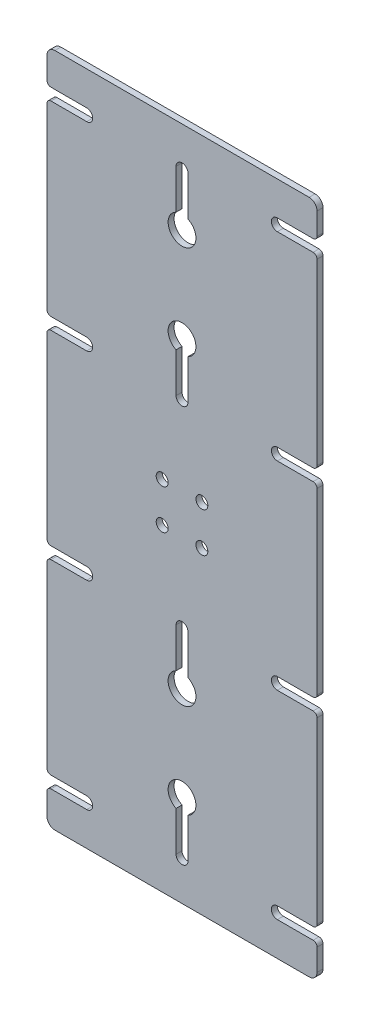
SolidWorks part; units mm, degrees
ref_plane "前视基准面" through (0, 0, 0) normal (0, 0, 1) x (1, 0, 0)
ref_plane "上视基准面" through (0, 0, 0) normal (0, 1, 0) x (1, 0, 0)
ref_plane "右视基准面" through (0, 0, 0) normal (1, 0, 0) x (0, 0, -1)
sketch "草图1" plane through (0, 0, 0) normal (0, 0, 1) x (1, 0, 0)
  line L0 (80, 90) -> (100, 90)
  line L1 (0, 0) -> (80, 0)
  line L2 (0, 0) -> (0, 70)
  line L3 (0, 160) -> (80, 160)
  line L4 (80, 0) -> (80, 70)
  line L5 (100, 90) -> (100, 70)
  line L6 (100, 70) -> (80, 70)
  line L7 (0, 70) -> (-20, 70)
  line L8 (-20, 70) -> (-20, 90)
  line L9 (-20, 90) -> (0, 90)
  line L10 (0, 90) -> (0, 160)
  line L11 (80, 90) -> (80, 160)
  dimension "D1" = 160
  dimension "D2" = 80
  dimension "D3" = 20
  dimension "D4" = 20
  dimension "D5" = 20
  dimension "D6" = 20
  dimension "D7" = 70
extrude "凸台-拉伸1" add sketch "草图1" along normal blind 1.5
sketch "草图2" plane through (0, 0, 1.5) normal (0, 0, 1) x (1, 0, 0)
  line L0 (0, 0) -> (80, 0) construction
  line L1 (0, 70) -> (0, 0) construction
  line L2 (64, 153.5) -> (80, 153.5)
  line L3 (38.5, 5) -> (38.5, 15)
  line L4 (80, 90) -> (80, 160) construction
  line L5 (64, 156.5) -> (80, 156.5)
  line L6 (16, 153.5) -> (0, 153.5)
  line L7 (0, 160) -> (0, 90) construction
  line L8 (16, 156.5) -> (0, 156.5)
  line L9 (64, 103.5) -> (80, 103.5)
  line L10 (64, 106.5) -> (80, 106.5)
  line L11 (16, 106.5) -> (0, 106.5)
  line L12 (16, 103.5) -> (0, 103.5)
  line L13 (16, 56.5) -> (0, 56.5)
  line L14 (16, 53.5) -> (0, 53.5)
  line L15 (64, 53.5) -> (80, 53.5)
  line L16 (80, 0) -> (80, 70) construction
  line L17 (64, 56.5) -> (80, 56.5)
  line L18 (16, 6.5) -> (0, 6.5)
  line L19 (16, 3.5) -> (0, 3.5)
  line L20 (64, 6.5) -> (80, 6.5)
  line L21 (64, 3.5) -> (80, 3.5)
  line L22 (80, 156.5) -> (80, 153.5)
  line L23 (0, 156.5) -> (0, 153.5)
  line L24 (0, 106.5) -> (0, 103.5)
  line L25 (80, 106.5) -> (80, 103.5)
  line L26 (80, 56.5) -> (80, 53.5)
  line L27 (0, 56.5) -> (0, 53.5)
  line L28 (0, 6.5) -> (0, 3.5)
  line L29 (80, 6.5) -> (80, 3.5)
  line L30 (41.5, 5) -> (41.5, 15)
  line L31 (32.0717, 15) -> (48.9361, 15) construction
  line L32 (40, 19.8903) -> (40, 12.1937) construction
  line L33 (6.3154, 80) -> (80, 80) construction
  line L34 (40, 113.7367) -> (40, 124.7584) construction
  line L35 (38.5, 155) -> (38.5, 145)
  line L36 (41.5, 155) -> (41.5, 145)
  line L37 (41.5, 55) -> (41.5, 45)
  line L38 (38.5, 55) -> (38.5, 45)
  line L39 (40, 46.2633) -> (40, 35.2416) construction
  line L40 (38.5, 105) -> (38.5, 115)
  line L41 (41.5, 105) -> (41.5, 115)
  arc A0 (64, 6.5) -> (64, 3.5) centre (64, 5) ccw
  arc A1 (64, 56.5) -> (64, 53.5) centre (64, 55) ccw
  arc A2 (64, 106.5) -> (64, 103.5) centre (64, 105) ccw
  arc A3 (64, 156.5) -> (64, 153.5) centre (64, 155) ccw
  arc A4 (16, 153.5) -> (16, 156.5) centre (16, 155) ccw
  arc A5 (16, 103.5) -> (16, 106.5) centre (16, 105) ccw
  arc A6 (16, 53.5) -> (16, 56.5) centre (16, 55) ccw
  arc A7 (16, 3.5) -> (16, 6.5) centre (16, 5) ccw
  arc A8 (41.5, 155) -> (38.5, 155) centre (40, 155) ccw
  arc A9 (38.5, 105) -> (41.5, 105) centre (40, 105) ccw
  arc A10 (41.5, 55) -> (38.5, 55) centre (40, 55) ccw
  arc A11 (38.5, 5) -> (41.5, 5) centre (40, 5) ccw
  arc A12 (41.5, 15) -> (38.5, 15) centre (40, 18.1623) ccw
  arc A13 (41.5, 145) -> (38.5, 145) centre (40, 141.8377) cw
  arc A14 (38.5, 45) -> (41.5, 45) centre (40, 41.8377) ccw
  arc A15 (38.5, 115) -> (41.5, 115) centre (40, 118.1623) cw
  dimension "D1" = 3
  dimension "D2" = 3
  dimension "D3" = 3
  dimension "D4" = 3
  dimension "D11" = 10
  dimension "D13" = 7
  dimension "D14" = 3
  dimension "D15" = 40
  dimension "D23" = 7
  dimension "D5" = 16
  dimension "D6" = 16
  dimension "D7" = 16
  dimension "D8" = 5
  dimension "D9" = 2
  dimension "D10" = 16
  dimension "D16" = 16
  dimension "D17" = 50
  dimension "D18" = 50
  dimension "D19" = 50
  dimension "D20" = 80
  dimension "D21" = 10
  dimension "D22" = 1.5
extrude "切除-拉伸1" cut sketch "草图2" against normal blind 1.5
sketch "草图3" plane through (0, 0, 1.5) normal (0, 0, 1) x (1, 0, 0)
  line L0 (0, 90) -> (-20, 90) construction
  line L2 (-20, 90) -> (-20, 70) construction
  line L3 (100, 70) -> (100, 90) construction
  line L4 (100, 90) -> (80, 90) construction
  circle A0 centre (90, 80) radius 2
  circle A1 centre (-10, 80) radius 2
  point P10 (100, 80)
  dimension "D1" = 4
  dimension "D2" = 4
  dimension "D4" = 10
  dimension "D5" = 10
  dimension "D6" = 10
  dimension "D3" = 10
extrude "切除-拉伸2" cut sketch "草图3" against normal blind 1.5
sketch "草图4" plane through (0, 0, 0) normal (0, 0, -1) x (-1, 0, 0)
  line L1 (0, 160) -> (-80, 160)
  line L2 (0, 160) -> (0, 165)
  line L3 (0, 165) -> (-80, 165)
  line L4 (-80, 160) -> (-80, 165)
  line L5 (0, 0) -> (-80, 0)
  line L6 (0, 0) -> (0, -5)
  line L7 (0, -5) -> (-80, -5)
  line L8 (-80, 0) -> (-80, -5)
  dimension "D1" = 5
  dimension "D2" = 5
extrude "凸台-拉伸2" add sketch "草图4" against normal blind 1.5
fillet "圆角1" radius 2 4 edges at (80, 165, 0.75) (0, 165, 0.75) (0, -5, 0.75) (80, -5, 0.75)
sketch "草图5" plane through (0, 0, 1.5) normal (0, 0, 1) x (1, 0, 0)
  line L0 (78, -5) -> (2, -5) construction
  line L1 (0, 165) -> (80, 165)
  line L2 (0, 165) -> (0, -5)
  line L3 (0, -5) -> (80, -5)
  line L4 (80, 165) -> (80, -5)
  line L5 (80, 6.5) -> (80, 53.5) construction
  line L6 (2, 165) -> (78, 165) construction
  line L7 (0, 153.5) -> (0, 106.5) construction
extrude "切除-拉伸3" cut sketch "草图5" against normal through all flip side to cut
sketch "草图6" plane through (0, 0, 0) normal (0, 0, -1) x (-1, 0, 0)
  line L0 (-80, 80) -> (26.8416, 80) construction
  line L1 (-80, 56.5) -> (-80, 103.5) construction
  line L2 (-40, -5) -> (-40, 194.401) construction
  line L3 (-78, -5) -> (-2, -5) construction
  circle A0 centre (-35, 85) radius 1.5
  circle A1 centre (-35, 75) radius 1.5
  circle A2 centre (-45, 75) radius 1.5
  circle A3 centre (-45, 85) radius 1.5
  dimension "D1" = 3
  dimension "D2" = 5
  dimension "D3" = 5
extrude "切除-拉伸4" cut sketch "草图6" against normal through all
sketch "草图7" plane through (0, 0, 1.5) normal (0, 0, 1) x (1, 0, 0)
  line L0 (2, 165) -> (78, 165) construction
  line L1 (0, -5) -> (6, -5)
  line L2 (0, -5) -> (0, 165)
  line L3 (0, 165) -> (6, 165)
  line L4 (6, -5) -> (6, 165)
  line L5 (78, -5) -> (2, -5) construction
  line L6 (80, 165) -> (74, 165)
  line L7 (80, 165) -> (80, -5)
  line L8 (80, -5) -> (74, -5)
  line L9 (74, 165) -> (74, -5)
  line L10 (80, 6.5) -> (80, 53.5) construction
  dimension "D1" = 6
  dimension "D2" = 6
  dimension "D3" = 0
extrude "切除-拉伸5" cut sketch "草图7" against normal blind 10
fillet "圆角2" radius 2 4 edges at (6, 165, 0.75) (74, 165, 0.75) (74, -5, 0.75) (6, -5, 0.75)
fillet "圆角3" radius 1 2 edges at (6, 153.5, 0.75) (6, 156.5, 0.75)
fillet "圆角4" radius 1 14 edges at (6, 103.5, 0.75) (6, 106.5, 0.75) (6, 53.5, 0.75) (6, 56.5, 0.75) (6, 6.5, 0.75) (6, 3.5, 0.75) (74, 3.5, 0.75) (74, 6.5, 0.75) (74, 53.5, 0.75) (74, 56.5, 0.75) (74, 103.5, 0.75) (74, 106.5, 0.75) (74, 153.5, 0.75) (74, 156.5, 0.75)
